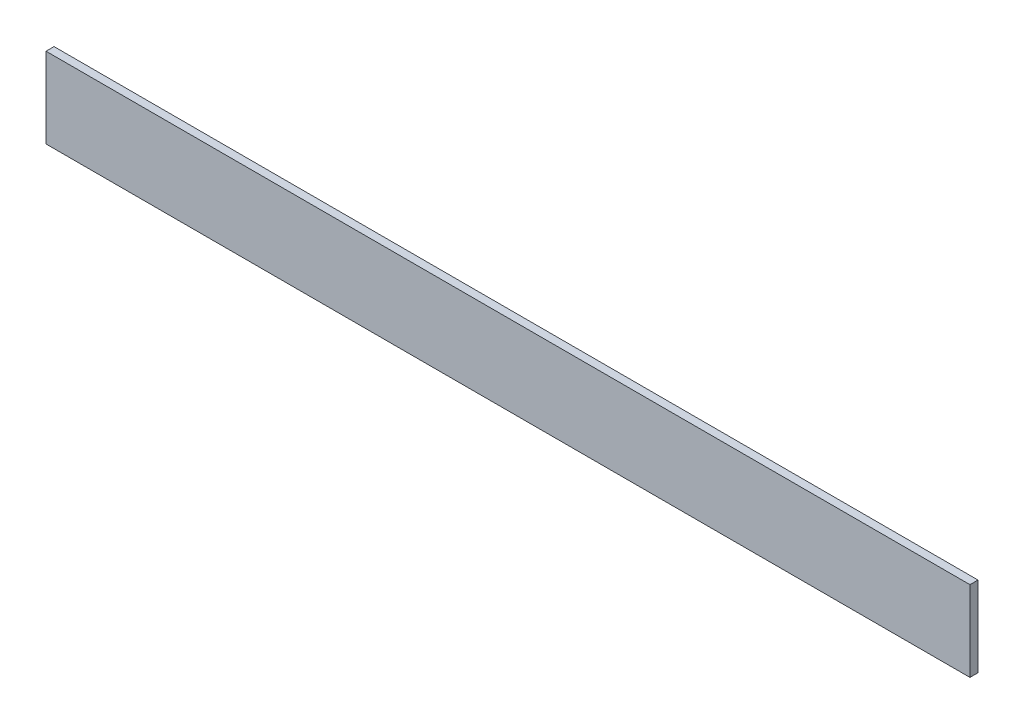
SolidWorks part; units mm, degrees
ref_plane "Front Plane" through (0, 0, 0) normal (0, 0, 1) x (1, 0, 0)
ref_plane "Top Plane" through (0, 0, 0) normal (0, 1, 0) x (1, 0, 0)
ref_plane "Right Plane" through (0, 0, 0) normal (1, 0, 0) x (0, 0, -1)
sketch "Sketch1" plane through (0, 0, 0) normal (0, 1, 0) x (1, 0, 0)
  line L1 (0, 0) -> (584.2, 0)
  line L2 (0, 0) -> (0, 5.08)
  line L3 (0, 5.08) -> (584.2, 5.08)
  line L4 (584.2, 0) -> (584.2, 5.08)
  dimension "D1" = 584.2
  dimension "D2" = 5.08
extrude "Boss-Extrude2" add sketch "Sketch1" along normal blind 50.8
